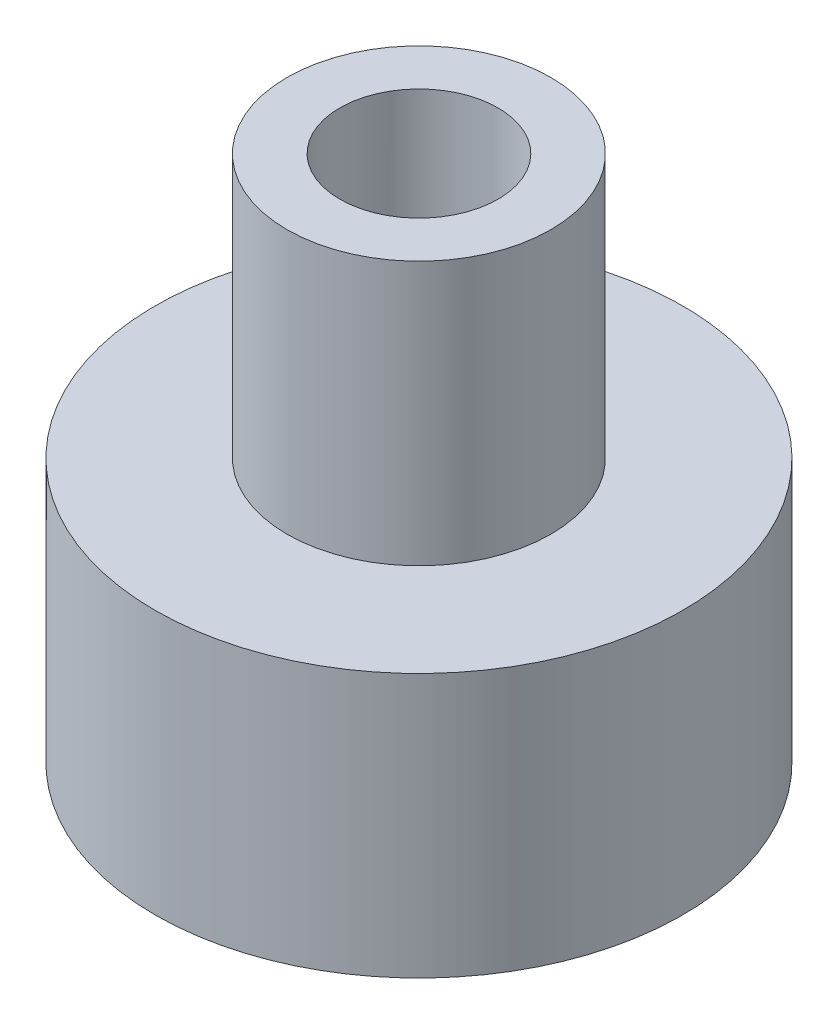
SolidWorks part; units mm, degrees
ref_plane "Front Plane" through (0, 0, 0) normal (0, 0, 1) x (1, 0, 0)
ref_plane "Top Plane" through (0, 0, 0) normal (0, 1, 0) x (1, 0, 0)
ref_plane "Right Plane" through (0, 0, 0) normal (1, 0, 0) x (0, 0, -1)
sketch "Esquisse1" plane through (0, 0, 0) normal (0, 1, 0) x (1, 0, 0)
  circle A0 centre (0, 0) radius 5
extrude "Boss.-Extru.1" add sketch "Esquisse1" along normal blind 5
sketch "Esquisse2" plane through (0, 5, 0) normal (0, 1, 0) x (1, 0, 0)
  circle A0 centre (0, 0) radius 2.5
extrude "Boss.-Extru.2" add sketch "Esquisse2" along normal blind 5
sketch "Esquisse3" plane through (0, 10, 0) normal (0, 1, 0) x (1, 0, 0)
  circle A0 centre (0, 0) radius 1.5
extrude "Enlèv. mat.-Extru.2" cut sketch "Esquisse3" against normal blind 5
sketch "Esquisse4" plane through (0, 0, 0) normal (0, -1, 0) x (1, 0, 0)
  circle A0 centre (0, 0) radius 2.05
extrude "Enlèv. mat.-Extru.3" cut sketch "Esquisse4" against normal blind 5
